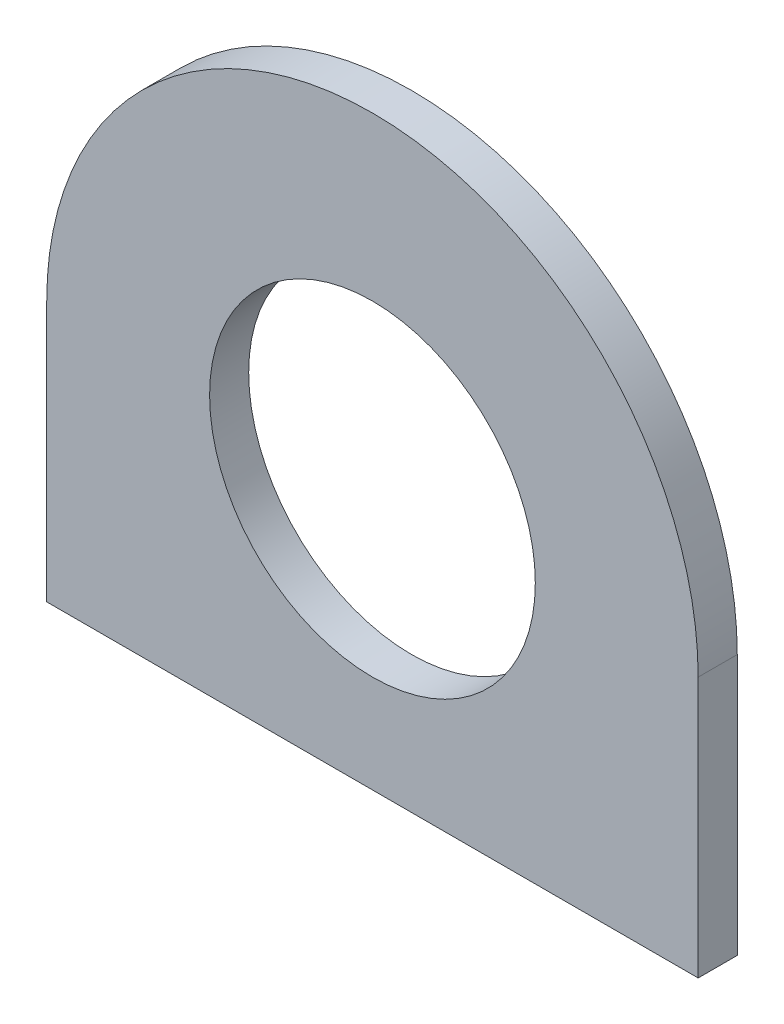
SolidWorks part; units mm, degrees
material "AISI 304"
ref_plane "Спереди" through (0, 0, 0) normal (0, 0, 1) x (1, 0, 0)
ref_plane "Сверху" through (0, 0, 0) normal (0, 1, 0) x (1, 0, 0)
ref_plane "Справа" through (0, 0, 0) normal (1, 0, 0) x (0, 0, -1)
sketch "Эскиз1" plane through (0, 0, 0) normal (0, 0, 1) x (1, 0, 0)
  line L0 (-50, 0) -> (-50, -40)
  line L1 (-50, -40) -> (50, -40)
  line L2 (50, -40) -> (50, 0)
  circle A0 centre (0, 0) radius 25
  arc A1 (50, 0) -> (-50, 0) centre (0, 0) ccw
  dimension "D1" = 50
  dimension "D2" = 50
  dimension "D3" = 40
extrude "Бобышка-Вытянуть1" add sketch "Эскиз1" along normal blind 6
